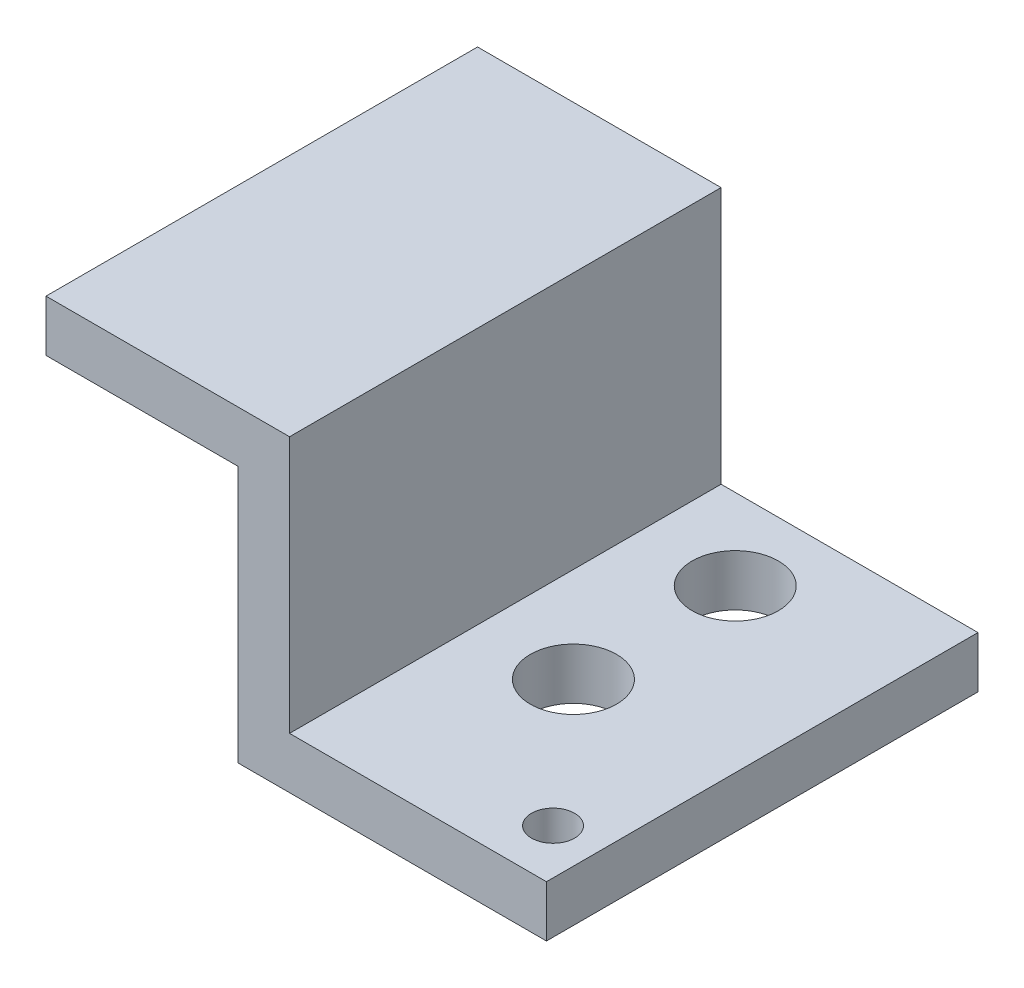
SolidWorks part; units mm, degrees
material "6061 Alloy"
ref_plane "Front Plane" through (0, 0, 0) normal (0, 0, 1) x (1, 0, 0)
ref_plane "Top Plane" through (0, 0, 0) normal (0, 1, 0) x (1, 0, 0)
ref_plane "Right Plane" through (0, 0, 0) normal (1, 0, 0) x (0, 0, -1)
sketch "Sketch1" plane through (0, 0, 0) normal (0, 0, 1) x (1, 0, 0)
  line L0 (0, -11.9062) -> (0, 11.9062) construction
  line L1 (0, 11.9062) -> (-26.1938, 11.9062) construction
  line L2 (0, -11.9062) -> (26.1938, -11.9062) construction
  line L3 (2.3812, -9.525) -> (26.1938, -9.525) construction
  line L4 (2.3812, -9.525) -> (2.3812, 14.2875) construction
  line L5 (2.3812, 14.2875) -> (-26.1938, 14.2875) construction
  line L6 (-2.3812, -14.2875) -> (26.1938, -14.2875) construction
  line L7 (-2.3812, -14.2875) -> (-2.3812, 9.525) construction
  line L8 (-2.3812, 9.525) -> (-26.1938, 9.525) construction
  line L9 (-26.1938, 14.2875) -> (-26.1938, 9.525) construction
  line L10 (26.1938, -9.525) -> (26.1938, -14.2875) construction
  point P4 (0, 0)
  dimension "Leg Width" = 28.575
  dimension "Outside Height" = 28.575
  dimension "Wall Thickness" = 4.7625
sketch "Sketch2" plane through (0, 0, 0) normal (1, 0, 0) x (0, 0, -1)
  line L0 (152.4, 0) -> (-152.4, 0) construction
  line L1 (0, 0) -> (0, 14.2875) construction
  line L2 (-152.4, 0) -> (-152.4, 14.2875) construction
  line L3 (152.4, 0) -> (152.4, 14.2875) construction
  point P0 (-114.3, 0)
  point P3 (114.3, 0)
  point P4 (0, 0)
  dimension "D1" = 228.6
  dimension "Length" = 304.8
sketch "Sketch3" plane through (0, 0, 0) normal (0, 0, 1) x (1, 0, 0)
  line L0 (26.1938, -9.525) -> (26.1938, -14.2875) construction
  line L1 (2.3812, -9.525) -> (26.1938, -9.525) construction
  line L2 (-2.3812, -14.2875) -> (26.1938, -14.2875) construction
  line L3 (-2.3812, -14.2875) -> (-2.3812, 9.525) construction
  line L4 (2.3812, -9.525) -> (2.3812, 14.2875) construction
  line L5 (2.3812, 14.2875) -> (-26.1938, 14.2875) construction
  line L6 (-26.1938, 14.2875) -> (-26.1938, 9.525) construction
  line L7 (-2.3812, 9.525) -> (-26.1938, 9.525) construction
  line L8 (26.1938, -9.525) -> (26.1938, -14.2875)
  line L9 (2.3812, -9.525) -> (26.1938, -9.525)
  line L10 (-2.3812, -14.2875) -> (26.1938, -14.2875)
  line L11 (-2.3812, -14.2875) -> (-2.3812, 9.525)
  line L12 (2.3812, -9.525) -> (2.3812, 14.2875)
  line L13 (2.3812, 14.2875) -> (-26.1938, 14.2875)
  line L14 (-26.1938, 14.2875) -> (-26.1938, 9.525)
  line L15 (-2.3812, 9.525) -> (-26.1938, 9.525)
extrude "Boss-Extrude1" add sketch "Sketch3" along normal blind 40
sketch "Sketch4" plane through (0, 14.2875, 0) normal (0, 1, 0) x (1, 0, 0)
  line L1 (-26.1938, -40) -> (-20.1937, -40)
  line L3 (2.3812, -40) -> (-26.1938, -40) construction
  line L5 (-26.1938, 0) -> (-26.1938, -40)
  line L8 (-26.1938, 0) -> (-20.1938, 0)
  line L9 (-20.1938, 0) -> (-20.1937, -40)
extrude "Cut-Extrude1" cut sketch "Sketch4" against normal up to surface (4.7625 mm away) up to face at (-14.2875, 9.525, 20)
sketch "Sketch5" plane through (0, -14.2875, 0) normal (0, -1, 0) x (1, 0, 0)
  line L0 (-2.3812, 0) -> (26.1938, 0) construction
  line L1 (-2.3812, 40) -> (-2.3812, 0) construction
  line L2 (26.1938, 40) -> (26.1938, 0) construction
  line L3 (-2.3812, 40) -> (26.1938, 40) construction
  circle A0 centre (11.1938, 7.5) radius 4
  circle A1 centre (11.1938, 22.5) radius 4
  circle A3 centre (22.0033, 35.1974) radius 2
  dimension "D1" = 7.5
  dimension "D2" = 15
  dimension "D3" = 15
  dimension "D5" = 4.8026
  dimension "D4" = 17.5
  dimension "D6" = 24.3846
extrude "Cut-Extrude2" cut sketch "Sketch5" against normal up to surface (4.7625 mm away) up to face at (14.2875, -9.525, 20)
equation "\"D1@Sketch2\"=\"Length@Sketch2\"*0.75"
